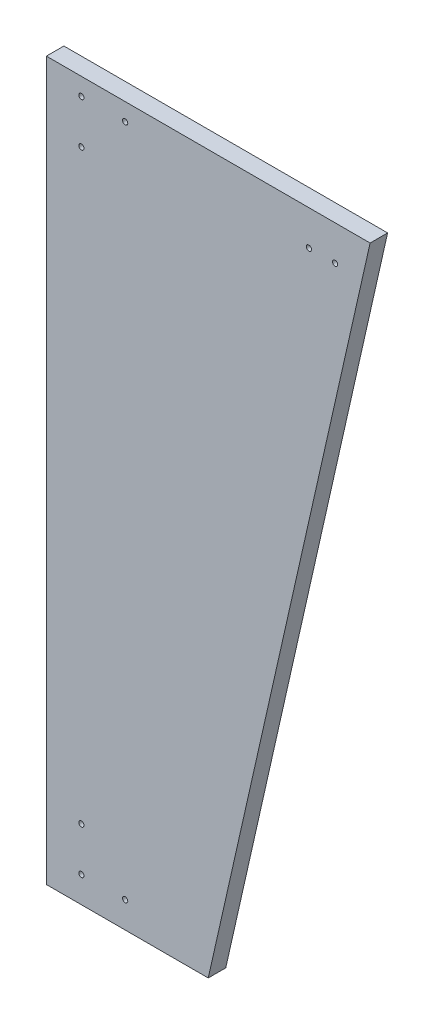
SolidWorks part; units mm, degrees
ref_plane "前视基准面" through (0, 0, 0) normal (0, 0, 1) x (1, 0, 0)
ref_plane "上视基准面" through (0, 0, 0) normal (0, 1, 0) x (1, 0, 0)
ref_plane "右视基准面" through (0, 0, 0) normal (1, 0, 0) x (0, 0, -1)
sketch "草图1" plane through (0, 0, 0) normal (0, 0, 1) x (1, 0, 0)
  line L0 (0, 0) -> (0, -400)
  line L2 (0, 0) -> (185, 0)
  line L4 (0, -400) -> (0, -410)
  line L5 (0, -410) -> (92.5, -410)
  line L6 (92.5, -410) -> (185, 0)
extrude "凸台-拉伸1" add sketch "草图1" along normal blind 10
sketch "草图2" plane through (0, 0, 10) normal (0, 0, 1) x (1, 0, 0)
  line L0 (0, 0) -> (0, -410) construction
  line L2 (20, -35) -> (20, -10) construction
  line L3 (20, -10) -> (45, -10) construction
  line L5 (20, -35) -> (45, -10) construction
  line L6 (20, -370) -> (20, -395) construction
  line L7 (0, 0) -> (185, 0) construction
  line L8 (20, -395) -> (45, -395) construction
  line L9 (0, -410) -> (92.5, -410) construction
  circle A0 centre (20, -35) radius 1.5
  circle A1 centre (45, -10) radius 1.5
  circle A2 centre (20, -10) radius 1.5
  circle A3 centre (45, -395) radius 1.5
  circle A4 centre (20, -395) radius 1.5
  circle A5 centre (20, -370) radius 1.5
  point P0 (33.9005, -21.0995)
  dimension "D5" = 3
  dimension "D6" = 3
  dimension "D7" = 3
  dimension "D1" = 25
  dimension "D2" = 25
  dimension "D3" = 20
  dimension "D4" = 10
  dimension "D8" = 25
  dimension "D9" = 25
  dimension "D10" = 15
  dimension "D11" = 20
extrude "切除-拉伸1" cut sketch "草图2" against normal blind 10
sketch "草图3" plane through (0, 0, 0) normal (0, 0, -1) x (-1, 0, 0)
  line L0 (-165, -20) -> (-150, -20) construction
  line L1 (0, 0) -> (-185, 0) construction
  line L3 (0, 0) -> (0, -410) construction
  circle A0 centre (-165, -20) radius 1.5
  circle A1 centre (-150, -20) radius 1.5
  dimension "D1" = 3
  dimension "D2" = 3
  dimension "D3" = 15
  dimension "D4" = 20
  dimension "D5" = 165
extrude "切除-拉伸2" cut sketch "草图3" against normal blind 10
